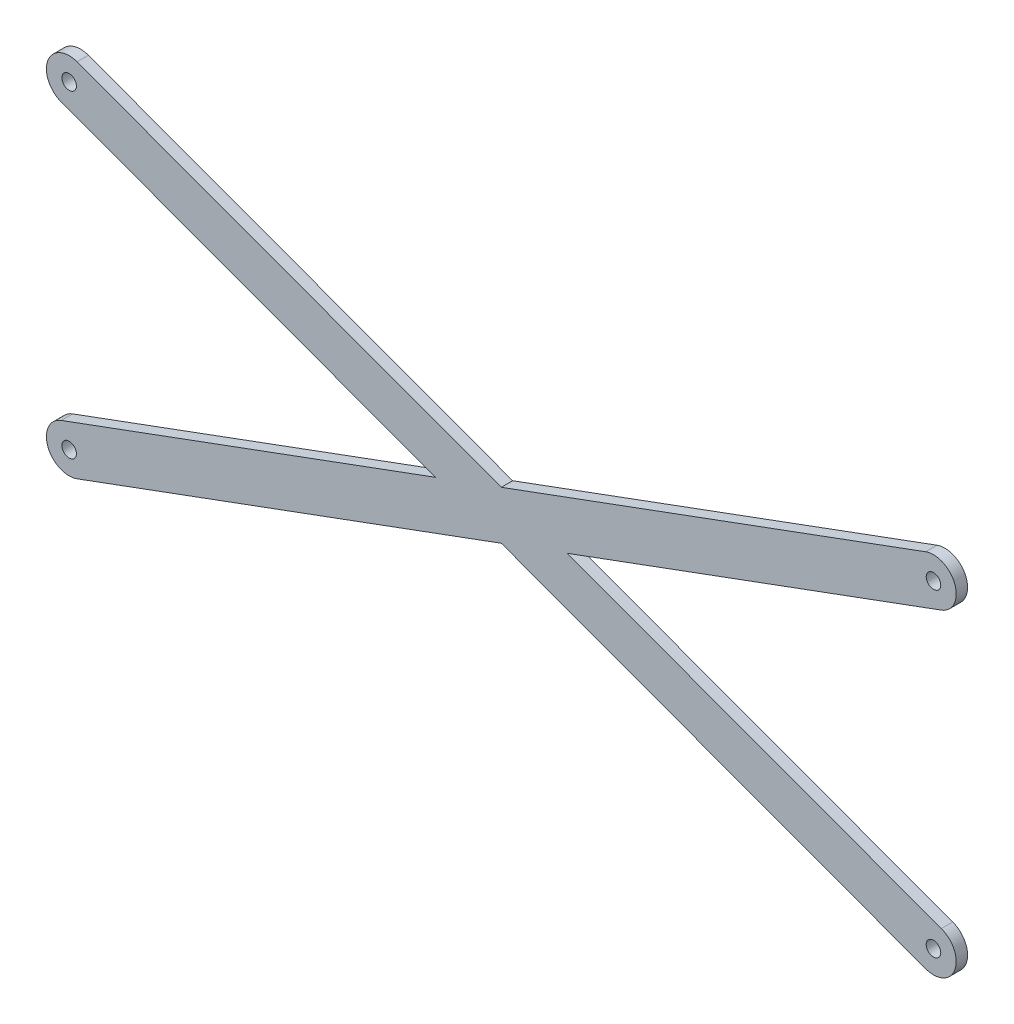
SolidWorks part; units mm, degrees
ref_plane "Front Plane" through (0, 0, 0) normal (0, 0, 1) x (1, 0, 0)
ref_plane "Top Plane" through (0, 0, 0) normal (0, 1, 0) x (1, 0, 0)
ref_plane "Right Plane" through (0, 0, 0) normal (1, 0, 0) x (0, 0, -1)
sketch "Sketch1" plane through (0, 0, 0) normal (0, 0, 1) x (1, 0, 0)
  line L0 (0, -88.9) -> (241.3, -0.0001) construction
  line L1 (-2.1952, -82.9415) -> (102.2818, -44.45)
  line L2 (2.1955, -94.8584) -> (120.65, -51.2173)
  line L3 (0, 0) -> (241.2997, -88.9) construction
  line L4 (2.1955, 5.9584) -> (120.65, -37.6828)
  line L5 (-2.1952, -5.9585) -> (102.2818, -44.45)
  line L6 (120.65, -51.2173) -> (239.1045, -94.8585)
  line L7 (120.65, -37.6828) -> (239.1046, 5.9583)
  line L8 (139.0182, -44.4501) -> (243.495, -82.9415)
  line L9 (139.0182, -44.4501) -> (243.4952, -5.9586)
  arc A0 (-2.1952, -82.9415) -> (2.1955, -94.8584) centre (0, -88.9) ccw
  arc A1 (243.4952, -5.9586) -> (239.1046, 5.9583) centre (241.3, -0.0001) ccw
  arc A2 (2.1955, 5.9584) -> (-2.1952, -5.9585) centre (0, 0) ccw
  arc A3 (239.1045, -94.8585) -> (243.495, -82.9415) centre (241.2997, -88.9) ccw
  point P2 (0, 0)
  point P9 (120.65, -44.4501)
  point P15 (0, 0)
  point P16 (129.7412, -47.216)
  point P21 (0, 0)
  point P22 (102.2819, -44.4498)
  point P23 (2.1953, -94.858)
  point P24 (-2.1952, -82.9415)
  point P25 (243.4945, -5.9585)
  point P26 (120.65, -37.6829)
  point P27 (139.0182, -44.4502)
  point P28 (139.0182, -44.4501)
  point P29 (-2.1952, -5.9587)
  point P30 (120.65, -51.2174)
  point P31 (102.2818, -44.4502)
  point P32 (0, -88.9)
  point P33 (2.1955, -94.8586)
  point P34 (243.4952, -82.9415)
  point P35 (120.65, -51.2173)
  point P36 (102.2818, -44.4501)
  point P37 (0, 0)
  point P38 (139.0182, -44.4501)
  dimension "D5" = 6.35
  dimension "D1" = 241.3
  dimension "D2" = 12.7
  dimension "D3" = 88.9
  dimension "D4" = 12.7
extrude "Boss-Extrude1" add sketch "Sketch1" along normal blind 3.175
sketch "Sketch2" plane through (0, 0, 3.175) normal (0, 0, 1) x (1, 0, 0)
  circle A0 centre (0, 0) radius 2.032
  circle A1 centre (0, -88.9) radius 2.032
  circle A2 centre (241.2997, -88.9) radius 2.032
  circle A3 centre (241.3, -0.0001) radius 2.032
  dimension "D1" = 4.064
extrude "Cut-Extrude1" cut sketch "Sketch2" against normal through all
